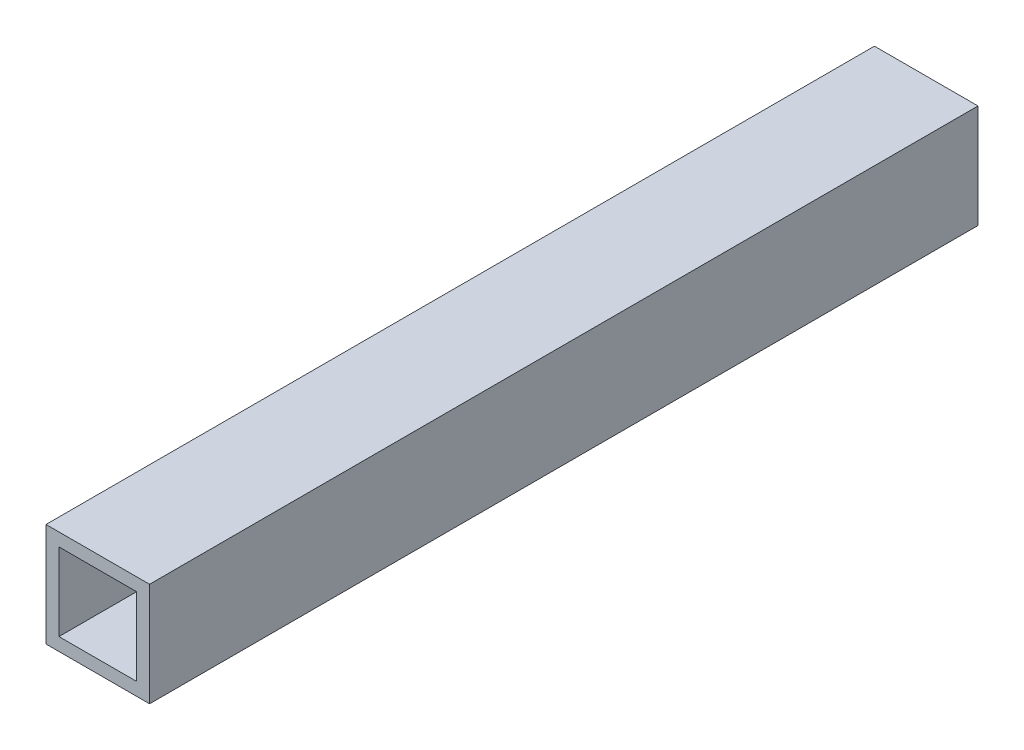
SolidWorks part; units mm, degrees
ref_plane "Front Plane" through (0, 0, 0) normal (0, 0, 1) x (1, 0, 0)
ref_plane "Top Plane" through (0, 0, 0) normal (0, 1, 0) x (1, 0, 0)
ref_plane "Right Plane" through (0, 0, 0) normal (1, 0, 0) x (0, 0, -1)
sketch "Sketch1" plane through (0, 0, 0) normal (0, 0, 1) x (1, 0, 0)
  line L1 (12.7, -12.7) -> (-12.7, -12.7)
  line L2 (12.7, -12.7) -> (12.7, 12.7)
  line L3 (12.7, 12.7) -> (-12.7, 12.7)
  line L4 (-12.7, -12.7) -> (-12.7, 12.7)
  line L5 (12.7, -12.7) -> (-12.7, 12.7) construction
  line L6 (12.7, 12.7) -> (-12.7, -12.7) construction
  line L7 (9.525, -9.525) -> (-9.525, -9.525)
  line L8 (9.525, -9.525) -> (9.525, 9.525)
  line L9 (9.525, 9.525) -> (-9.525, 9.525)
  line L10 (-9.525, -9.525) -> (-9.525, 9.525)
  line L11 (9.525, -9.525) -> (-9.525, 9.525) construction
  line L12 (9.525, 9.525) -> (-9.525, -9.525) construction
  point P0 (0, 0)
  point P6 (0, 0)
  dimension "D1" = 3.175
  dimension "D2" = 25.4
  dimension "D3" = 25.4
extrude "Boss-Extrude1" add sketch "Sketch1" along normal blind 203.2
